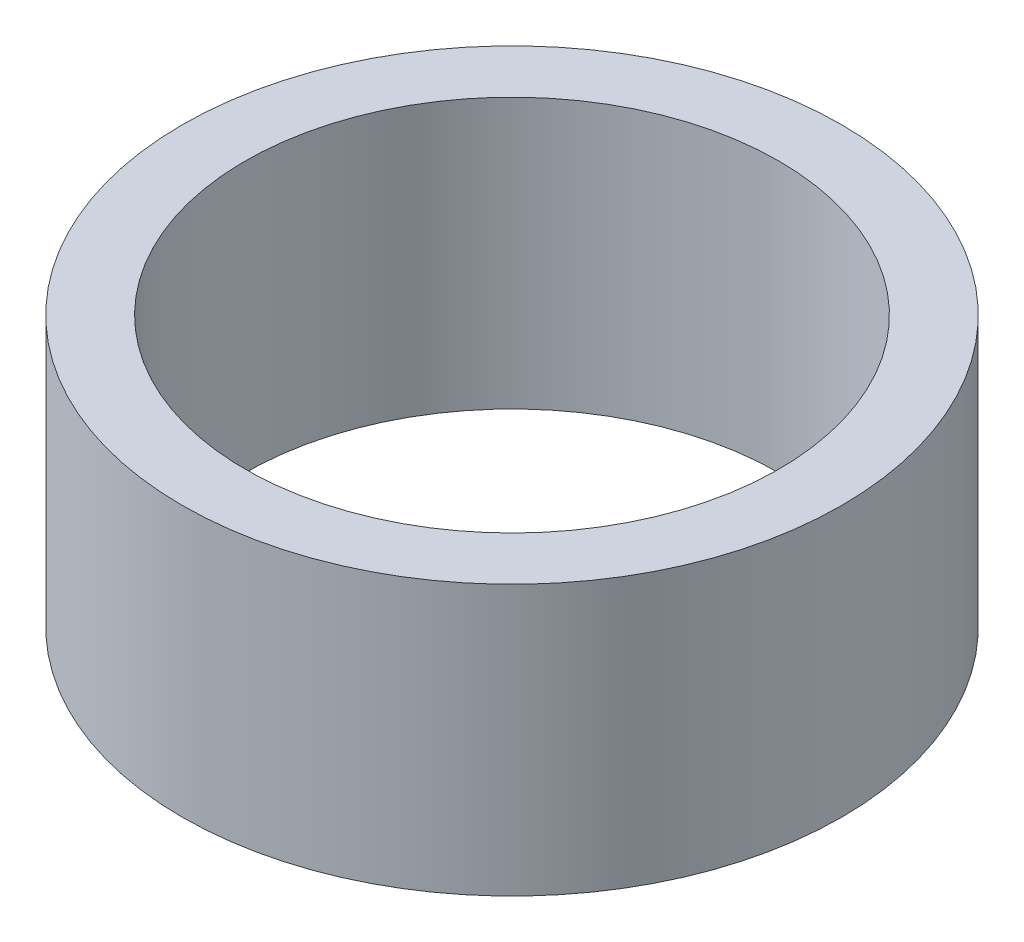
SolidWorks part; units mm, degrees
material "硅橡胶"
ref_plane "前视基准面" through (0, 0, 0) normal (0, 0, 1) x (1, 0, 0)
ref_plane "上视基准面" through (0, 0, 0) normal (0, 1, 0) x (1, 0, 0)
ref_plane "右视基准面" through (0, 0, 0) normal (1, 0, 0) x (0, 0, -1)
sketch "草图1" plane through (0, 0, 0) normal (0, 1, 0) x (1, 0, 0)
  circle A0 centre (0, 0) radius 31.5
  circle A1 centre (0, 0) radius 25.5
  dimension "D1" = 51
  dimension "D2" = 63
extrude "凸台-拉伸1" add sketch "草图1" along normal blind 25.8
